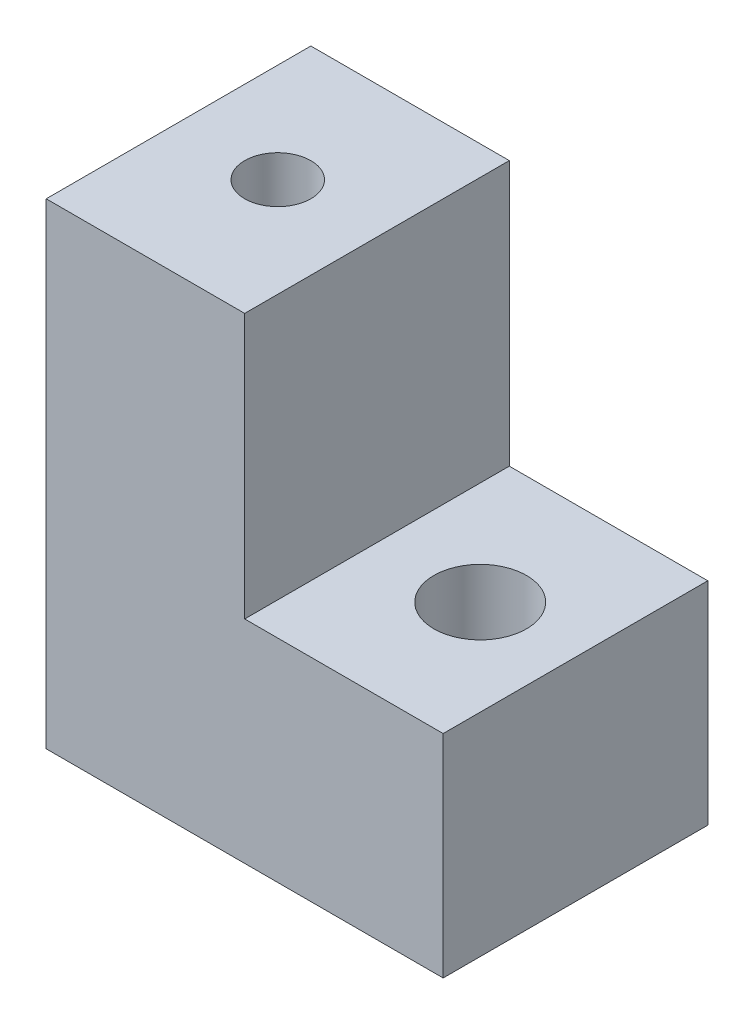
SolidWorks part; units mm, degrees
ref_plane "Front Plane" through (0, 0, 0) normal (0, 0, 1) x (1, 0, 0)
ref_plane "Top Plane" through (0, 0, 0) normal (0, 1, 0) x (1, 0, 0)
ref_plane "Right Plane" through (0, 0, 0) normal (1, 0, 0) x (0, 0, -1)
sketch "Sketch1" plane through (0, 0, 0) normal (0, 0, 1) x (1, 0, 0)
  line L10 (0, 0) -> (-15, 0)
  line L11 (55, 0) -> (-55, 0) construction
  line L12 (-15, 0) -> (-15, 18)
  line L13 (-15, 18) -> (-7.5, 18)
  line L14 (-7.5, 18) -> (-7.5, 8)
  line L15 (-7.5, 8) -> (0, 8)
  line L16 (0, -44.7868) -> (0, 44.7868) construction
  line L17 (0, 8) -> (0, 0)
  dimension "D1" = 15
  dimension "D2" = 7.5
  dimension "D3" = 18
  dimension "D4" = 8
extrude "Boss-Extrude1" add sketch "Sketch1" along normal blind 10 contours L17 L10 L12 L13 L14 L15
sketch "Sketch6" plane through (0, 8, 0) normal (0, 1, 0) x (1, 0, 0)
  line L0 (-7.5, -10) -> (-7.5, 0) construction
  line L1 (-7.5, -10) -> (0, -10) construction
  circle A0 centre (-3.6, -5) radius 1.75
  dimension "D1" = 3.5
  dimension "D2" = 3.9
  dimension "D3" = 5
extrude "Cut-Extrude1" cut sketch "Sketch6" against normal blind 6
hole_wizard "Ø2.5mm Dowel Hole1" positions "Sketch7" profile "Sketch8" hole size "Ø2.5" standard "ISO" end condition through all
sketch "Sketch7" plane through (0, 2, 0) normal (0, 1, 0) x (1, 0, 0)
  line L0 (-7.5, -10) -> (-7.5, 0) construction
  line L1 (-7.5, -10) -> (0, -10) construction
  point P0 (-3.6, -5)
  point P5 (-7.5, -5)
  dimension "D1" = 3.9
  dimension "D2" = 5
sketch "Sketch8" plane through (-3.6, 2, 5) normal (1, 0, 0) x (0, 0, 1)
  line L0 (0, 0) -> (0, 2)
  line L1 (0, 2) -> (1.25, 2)
  line L2 (1.25, 2) -> (1.25, 0)
  line L5 (1.25, 0) -> (0, 0)
  line L11 (0, -6.35) -> (0, 107.95) construction
  dimension "Thru Hole Dia." = 2.5
  dimension "Thru Hole Depth" = 2
sketch "Sketch9" plane through (0, 0, 0) normal (0, -1, 0) x (1, 0, 0)
  line L0 (0, 10) -> (-15, 10) construction
  line L1 (-15, 10) -> (-15, 0) construction
  circle A0 centre (-11.25, 5) radius 1.75
  dimension "D1" = 3.5
  dimension "D2" = 5
  dimension "D3" = 3.75
extrude "Cut-Extrude2" cut sketch "Sketch9" against normal blind 15
hole_wizard "Ø2.5mm Dowel Hole2" positions "Sketch10" profile "Sketch11" hole size "Ø2.5" standard "ISO" end condition through all
sketch "Sketch10" plane through (0, 15, 0) normal (0, -1, 0) x (-1, 0, 0)
  line L0 (15, -10) -> (15, 0) construction
  line L1 (0, -10) -> (15, -10) construction
  point P0 (11.25, -5)
  dimension "D1" = 3.75
  dimension "D2" = 5
sketch "Sketch11" plane through (-11.25, 15, 5) normal (1, 0, 0) x (0, 0, -1)
  line L0 (0, 0) -> (0, 3)
  line L1 (0, 3) -> (1.25, 3)
  line L2 (1.25, 3) -> (1.25, 0)
  line L5 (1.25, 0) -> (0, 0)
  line L11 (0, -6.35) -> (0, 107.95) construction
  dimension "Thru Hole Dia." = 2.5
  dimension "Thru Hole Depth" = 3
hole_wizard "CSK for M2.5 Countersunk Flat Head Screw1" positions "Sketch4" profile "Sketch5" countersink size "M2.5" standard "ISO"
sketch "Sketch4" plane through (0, 8, 0) normal (0, 1, 0) x (1, 0, 0)
  point P0 (-3.8264, -5.0154)
sketch "Sketch5" plane through (-3.8264, 8, 5.0154) normal (1, 0, 0) x (0, 0, 1)
  line L0 (0, 0) -> (0, 8)
  line L1 (0, 8) -> (1.45, 8)
  line L2 (1.45, 8) -> (1.45, 1.3)
  line L3 (1.45, 1.3) -> (2.75, 0)
  line L5 (2.75, 0) -> (0, 0)
  line L6 (-1.45, 1.3) -> (-2.75, 0) construction
  line L11 (0, -6.35) -> (0, 107.95) construction
  dimension "Thru Hole Dia." = 2.9
  dimension "Thru Hole Depth" = 8
  dimension "Near C'Sink Dia." = 5.5
  dimension "Near C'Sink Angle" = 90
